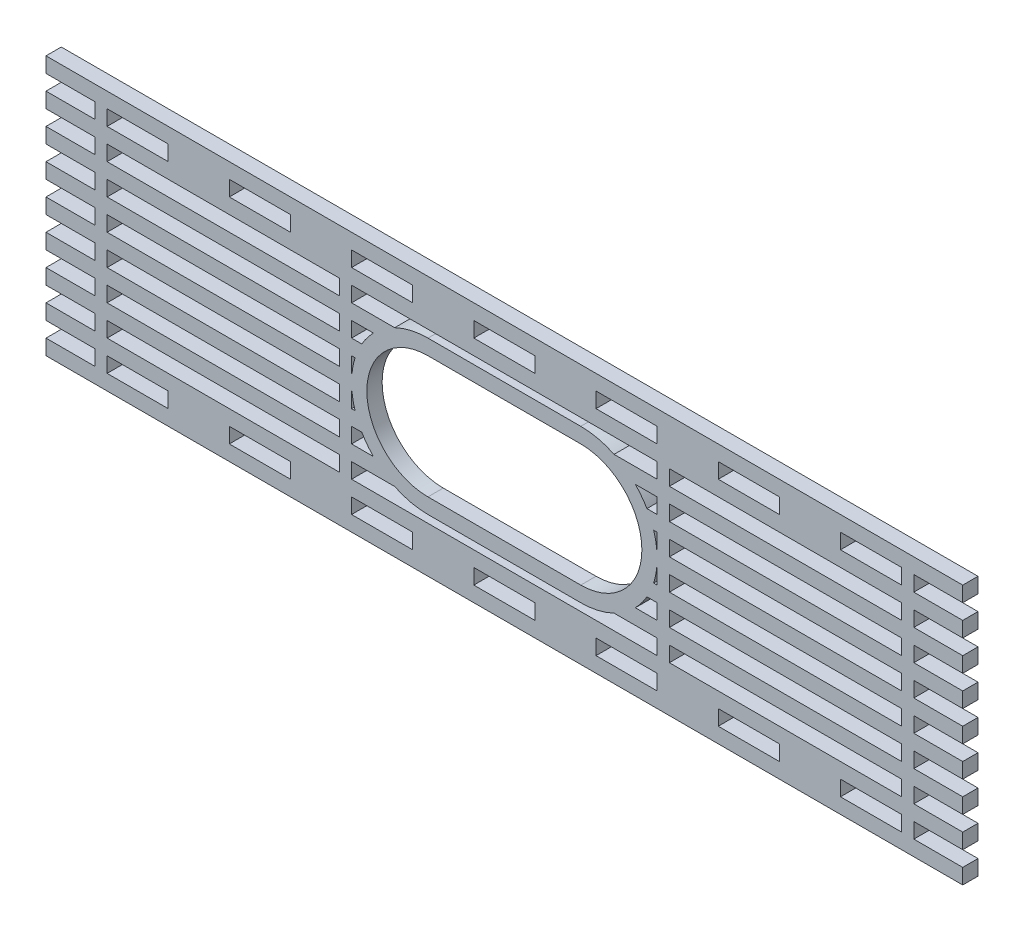
SolidWorks part; units mm, degrees
material "Maple"
ref_plane "Front Plane" through (0, 0, 0) normal (0, 0, 1) x (1, 0, 0)
ref_plane "Top Plane" through (0, 0, 0) normal (0, 1, 0) x (1, 0, 0)
ref_plane "Right Plane" through (0, 0, 0) normal (1, 0, 0) x (0, 0, -1)
sketch "Sketch1" plane through (0, 0, 0) normal (0, 0, 1) x (1, 0, 0)
  line L0 (-12.5, 0) -> (12.5, 0) construction
  line L1 (-75, -21.25) -> (75, -21.25) construction
  line L2 (-75, -21.25) -> (-75, 21.25) construction
  line L3 (-75, 21.25) -> (75, 21.25) construction
  line L4 (75, -21.25) -> (75, 21.25) construction
  line L5 (-75, -21.25) -> (75, 21.25) construction
  line L6 (-75, 21.25) -> (75, -21.25) construction
  line L7 (-12.5, 10) -> (12.5, 10)
  line L8 (-12.5, -10) -> (12.5, -10)
  line L9 (0, -10) -> (0, 10) construction
  line L10 (-22.5, 21.25) -> (-22.5, -21.25) construction
  line L11 (22.5, 21.25) -> (22.5, -21.25) construction
  line L12 (-75, 18.75) -> (-22.5, 18.75) construction
  line L13 (75, 18.75) -> (22.5, 18.75) construction
  line L14 (-75, 16.25) -> (-22.5, 16.25) construction
  line L15 (75, 16.25) -> (22.5, 16.25) construction
  line L16 (-75, 13.75) -> (-22.5, 13.75) construction
  line L18 (-75, 11.25) -> (-22.5, 11.25) construction
  line L20 (-75, 8.75) -> (-22.5, 8.75) construction
  line L22 (-75, 6.25) -> (-22.5, 6.25) construction
  line L24 (-75, 3.75) -> (-22.5, 3.75) construction
  line L26 (-75, 1.25) -> (-22.5, 1.25) construction
  line L44 (-22.5, 18.75) -> (22.5, 18.75) construction
  line L45 (-22.5, 16.25) -> (22.5, 16.25) construction
  line L46 (-22.5, 13.75) -> (22.5, 13.75) construction
  line L47 (-22.5, 11.25) -> (22.5, 11.25) construction
  line L48 (-22.5, -18.75) -> (22.5, -18.75) construction
  line L49 (-22.5, -16.25) -> (22.5, -16.25) construction
  line L50 (-22.5, -13.75) -> (22.5, -13.75) construction
  line L51 (-22.5, -11.25) -> (22.5, -11.25) construction
  line L52 (-27, 0) -> (29.3489, 0) construction
  line L53 (-5, -18.75) -> (5, -18.75)
  line L54 (-5, -18.75) -> (-5, -16.25)
  line L55 (-5, -16.25) -> (5, -16.25)
  line L56 (5, -18.75) -> (5, -16.25)
  line L57 (-5, -18.75) -> (5, -16.25) construction
  line L58 (-5, -16.25) -> (5, -18.75) construction
  line L59 (-5, 16.25) -> (5, 16.25)
  line L60 (5, 18.75) -> (5, 16.25)
  line L61 (-5, 18.75) -> (5, 18.75)
  line L62 (-5, 18.75) -> (-5, 16.25)
  line L63 (15, 16.25) -> (25, 16.25)
  line L64 (25, 18.75) -> (25, 16.25)
  line L65 (15, 18.75) -> (25, 18.75)
  line L66 (15, 18.75) -> (15, 16.25)
  line L67 (15, -18.75) -> (25, -18.75)
  line L68 (25, -18.75) -> (25, -16.25)
  line L69 (15, -16.25) -> (25, -16.25)
  line L70 (15, -18.75) -> (15, -16.25)
  line L71 (35, 16.25) -> (45, 16.25)
  line L72 (45, 18.75) -> (45, 16.25)
  line L73 (35, 18.75) -> (45, 18.75)
  line L74 (35, 18.75) -> (35, 16.25)
  line L75 (35, -18.75) -> (45, -18.75)
  line L76 (45, -18.75) -> (45, -16.25)
  line L77 (35, -16.25) -> (45, -16.25)
  line L78 (35, -18.75) -> (35, -16.25)
  line L79 (55, 16.25) -> (65, 16.25)
  line L80 (65, 18.75) -> (65, 16.25)
  line L81 (55, 18.75) -> (65, 18.75)
  line L82 (55, 18.75) -> (55, 16.25)
  line L83 (55, -18.75) -> (65, -18.75)
  line L84 (65, -18.75) -> (65, -16.25)
  line L85 (55, -16.25) -> (65, -16.25)
  line L86 (55, -18.75) -> (55, -16.25)
  line L87 (-25, -18.75) -> (-15, -18.75)
  line L88 (-15, -18.75) -> (-15, -16.25)
  line L89 (-25, -16.25) -> (-15, -16.25)
  line L90 (-25, -18.75) -> (-25, -16.25)
  line L91 (-25, 16.25) -> (-15, 16.25)
  line L92 (-15, 18.75) -> (-15, 16.25)
  line L93 (-25, 18.75) -> (-15, 18.75)
  line L94 (-25, 18.75) -> (-25, 16.25)
  line L95 (-45, -18.75) -> (-35, -18.75)
  line L96 (-35, -18.75) -> (-35, -16.25)
  line L97 (-45, -16.25) -> (-35, -16.25)
  line L98 (-45, -18.75) -> (-45, -16.25)
  line L99 (-45, 16.25) -> (-35, 16.25)
  line L100 (-35, 18.75) -> (-35, 16.25)
  line L101 (-45, 18.75) -> (-35, 18.75)
  line L102 (-45, 18.75) -> (-45, 16.25)
  line L103 (-65, -18.75) -> (-55, -18.75)
  line L104 (-55, -18.75) -> (-55, -16.25)
  line L105 (-65, -16.25) -> (-55, -16.25)
  line L106 (-65, -18.75) -> (-65, -16.25)
  line L107 (-65, 16.25) -> (-55, 16.25)
  line L108 (-55, 18.75) -> (-55, 16.25)
  line L109 (-65, 18.75) -> (-55, 18.75)
  line L110 (-65, 18.75) -> (-65, 16.25)
  line L111 (-67, 21.25) -> (-67, -21.25) construction
  line L112 (67, 21.25) -> (67, -21.25) construction
  line L113 (75, 21.25) -> (-75, 21.25)
  line L114 (-75, 21.25) -> (-75, 18.75)
  line L115 (-75, 18.75) -> (-67, 18.75)
  line L116 (-67, 18.75) -> (-67, 16.25)
  line L117 (-67, 16.25) -> (-75, 16.25)
  line L118 (-75, 16.25) -> (-75, 13.75)
  line L119 (-75, 13.75) -> (-67, 13.75)
  line L120 (-67, 13.75) -> (-67, 11.25)
  line L121 (-67, 11.25) -> (-75, 11.25)
  line L122 (-75, 11.25) -> (-75, 8.75)
  line L123 (-75, 8.75) -> (-67, 8.75)
  line L124 (-67, 8.75) -> (-67, 6.25)
  line L125 (-67, 6.25) -> (-75, 6.25)
  line L126 (-75, 6.25) -> (-75, 3.75)
  line L127 (-75, 3.75) -> (-67, 3.75)
  line L128 (-67, 3.75) -> (-67, 1.25)
  line L129 (-67, 1.25) -> (-75, 1.25)
  line L130 (-75, 1.25) -> (-75, -1.25)
  line L131 (-67, -1.25) -> (-75, -1.25)
  line L132 (-67, -3.75) -> (-67, -1.25)
  line L133 (-75, -3.75) -> (-67, -3.75)
  line L134 (-75, -6.25) -> (-75, -3.75)
  line L135 (-67, -6.25) -> (-75, -6.25)
  line L136 (-67, -8.75) -> (-67, -6.25)
  line L137 (-75, -8.75) -> (-67, -8.75)
  line L138 (-75, -11.25) -> (-75, -8.75)
  line L139 (-67, -11.25) -> (-75, -11.25)
  line L140 (-67, -13.75) -> (-67, -11.25)
  line L141 (-75, -13.75) -> (-67, -13.75)
  line L142 (-75, -16.25) -> (-75, -13.75)
  line L143 (-67, -16.25) -> (-75, -16.25)
  line L144 (-67, -18.75) -> (-67, -16.25)
  line L145 (-75, -18.75) -> (-67, -18.75)
  line L146 (-75, -21.25) -> (-75, -18.75)
  line L147 (75, -21.25) -> (-75, -21.25)
  line L148 (75, 13.75) -> (22.5, 13.75) construction
  line L149 (75, 11.25) -> (22.5, 11.25) construction
  line L150 (75, 8.75) -> (22.5, 8.75) construction
  line L151 (75, 6.25) -> (22.5, 6.25) construction
  line L152 (75, 3.75) -> (22.5, 3.75) construction
  line L153 (75, 1.25) -> (22.5, 1.25) construction
  line L228 (75, -21.25) -> (75, -18.75)
  line L229 (75, -18.75) -> (67, -18.75)
  line L230 (67, -18.75) -> (67, -16.25)
  line L231 (67, -16.25) -> (75, -16.25)
  line L232 (75, -16.25) -> (75, -13.75)
  line L233 (75, -13.75) -> (67, -13.75)
  line L234 (67, -13.75) -> (67, -11.25)
  line L235 (67, -11.25) -> (75, -11.25)
  line L236 (75, -11.25) -> (75, -8.75)
  line L237 (75, -8.75) -> (67, -8.75)
  line L238 (67, -8.75) -> (67, -6.25)
  line L239 (67, -6.25) -> (75, -6.25)
  line L240 (75, -6.25) -> (75, -3.75)
  line L241 (75, -3.75) -> (67, -3.75)
  line L242 (67, -3.75) -> (67, -1.25)
  line L243 (67, -1.25) -> (75, -1.25)
  line L244 (75, 1.25) -> (75, -1.25)
  line L245 (67, 1.25) -> (75, 1.25)
  line L246 (67, 3.75) -> (67, 1.25)
  line L247 (75, 3.75) -> (67, 3.75)
  line L248 (75, 6.25) -> (75, 3.75)
  line L249 (67, 6.25) -> (75, 6.25)
  line L250 (67, 8.75) -> (67, 6.25)
  line L251 (75, 8.75) -> (67, 8.75)
  line L252 (75, 11.25) -> (75, 8.75)
  line L253 (67, 11.25) -> (75, 11.25)
  line L254 (67, 13.75) -> (67, 11.25)
  line L255 (75, 13.75) -> (67, 13.75)
  line L256 (75, 16.25) -> (75, 13.75)
  line L257 (67, 16.25) -> (75, 16.25)
  line L258 (67, 18.75) -> (67, 16.25)
  line L259 (75, 18.75) -> (67, 18.75)
  line L260 (75, 21.25) -> (75, 18.75)
  line L261 (-12.5, 12.5) -> (12.5, 12.5)
  line L262 (-12.5, -12.5) -> (12.5, -12.5)
  line L263 (-65, 21.25) -> (-65, 1.25) construction
  line L264 (-27, 21.25) -> (-27, 1.25) construction
  line L265 (-65, 8.75) -> (-65, 6.25)
  line L266 (-65, 13.75) -> (-27, 13.75)
  line L267 (-65, 13.75) -> (-65, 11.25)
  line L268 (25, -13.75) -> (25, -11.25)
  line L269 (25, -11.25) -> (17.9486, -11.25)
  line L270 (-17.9486, -11.25) -> (-25, -11.25)
  line L271 (-25, -11.25) -> (-25, -13.75)
  line L272 (-25, -13.75) -> (25, -13.75)
  line L273 (-65, 11.25) -> (-27, 11.25)
  line L274 (-27, 13.75) -> (-27, 11.25)
  line L275 (-65, 8.75) -> (-27, 8.75)
  line L276 (-25, 11.25) -> (-25, 13.75)
  line L277 (-17.9486, 11.25) -> (-25, 11.25)
  line L278 (-27, 8.75) -> (-27, 6.25)
  line L279 (-65, 6.25) -> (-27, 6.25)
  line L280 (-65, 3.75) -> (-65, 1.25)
  line L281 (25, 11.25) -> (17.9486, 11.25)
  line L282 (25, 13.75) -> (25, 11.25)
  line L283 (-25, 13.75) -> (25, 13.75)
  line L284 (-65, 3.75) -> (-27, 3.75)
  line L285 (-27, 3.75) -> (-27, 1.25)
  line L286 (-65, 1.25) -> (-27, 1.25)
  line L287 (-65, -3.75) -> (-27, -3.75)
  line L288 (-27, -3.75) -> (-27, -1.25)
  line L289 (-65, -1.25) -> (-27, -1.25)
  line L290 (-65, -3.75) -> (-65, -1.25)
  line L291 (-65, -8.75) -> (-27, -8.75)
  line L292 (-27, -8.75) -> (-27, -6.25)
  line L293 (-65, -6.25) -> (-27, -6.25)
  line L294 (-65, -8.75) -> (-65, -6.25)
  line L295 (-65, -11.25) -> (-27, -11.25)
  line L296 (-27, -13.75) -> (-27, -11.25)
  line L297 (-65, -13.75) -> (-27, -13.75)
  line L298 (-65, -13.75) -> (-65, -11.25)
  line L299 (65, 11.25) -> (27, 11.25)
  line L300 (27, 13.75) -> (27, 11.25)
  line L301 (65, 13.75) -> (27, 13.75)
  line L302 (65, 13.75) -> (65, 11.25)
  line L303 (65, 8.75) -> (27, 8.75)
  line L304 (27, 8.75) -> (27, 6.25)
  line L305 (65, 6.25) -> (27, 6.25)
  line L306 (65, 8.75) -> (65, 6.25)
  line L307 (65, 3.75) -> (27, 3.75)
  line L308 (27, 3.75) -> (27, 1.25)
  line L309 (65, 1.25) -> (27, 1.25)
  line L310 (65, 3.75) -> (65, 1.25)
  line L311 (65, -3.75) -> (65, -1.25)
  line L312 (65, -1.25) -> (27, -1.25)
  line L313 (27, -3.75) -> (27, -1.25)
  line L314 (65, -3.75) -> (27, -3.75)
  line L315 (65, -8.75) -> (65, -6.25)
  line L316 (65, -6.25) -> (27, -6.25)
  line L317 (27, -8.75) -> (27, -6.25)
  line L318 (65, -8.75) -> (27, -8.75)
  line L319 (65, -13.75) -> (65, -11.25)
  line L320 (65, -13.75) -> (27, -13.75)
  line L321 (27, -13.75) -> (27, -11.25)
  line L322 (65, -11.25) -> (27, -11.25)
  line L323 (-21.4268, 8.75) -> (-25, 8.75)
  line L324 (-25, 8.75) -> (-25, 6.25)
  line L325 (-25, 6.25) -> (-23.3253, 6.25)
  line L326 (-24.4242, 3.75) -> (-25, 3.75)
  line L327 (-25, 3.75) -> (-25, 1.25)
  line L328 (-25, 1.25) -> (-24.9373, 1.25)
  line L329 (-25, -1.25) -> (-24.9373, -1.25)
  line L330 (-25, -3.75) -> (-25, -1.25)
  line L331 (-24.4242, -3.75) -> (-25, -3.75)
  line L332 (-25, -6.25) -> (-23.3253, -6.25)
  line L333 (-25, -8.75) -> (-25, -6.25)
  line L334 (-21.4268, -8.75) -> (-25, -8.75)
  line L335 (25, -6.25) -> (23.3253, -6.25)
  line L336 (25, -8.75) -> (25, -6.25)
  line L337 (21.4268, -8.75) -> (25, -8.75)
  line L338 (25, -1.25) -> (24.9373, -1.25)
  line L339 (25, -3.75) -> (25, -1.25)
  line L340 (24.4242, -3.75) -> (25, -3.75)
  line L341 (25, 1.25) -> (24.9373, 1.25)
  line L342 (25, 3.75) -> (25, 1.25)
  line L343 (24.4242, 3.75) -> (25, 3.75)
  line L344 (-75, -21.25) -> (-75, -18.75)
  line L345 (-75, -18.75) -> (-67, -18.75)
  line L346 (-67, -18.75) -> (-67, -16.25)
  line L347 (-67, -16.25) -> (-75, -16.25)
  line L348 (-75, -16.25) -> (-75, -13.75)
  line L349 (-75, -13.75) -> (-67, -13.75)
  line L350 (-67, -13.75) -> (-67, -11.25)
  line L351 (-67, -11.25) -> (-75, -11.25)
  line L352 (-75, -11.25) -> (-75, -8.75)
  line L353 (-75, -8.75) -> (-67, -8.75)
  line L354 (-67, -8.75) -> (-67, -6.25)
  line L355 (-67, -6.25) -> (-75, -6.25)
  line L356 (-75, -6.25) -> (-75, -3.75)
  line L357 (-75, -3.75) -> (-67, -3.75)
  line L358 (-67, -3.75) -> (-67, -1.25)
  line L359 (-67, -1.25) -> (-75, -1.25)
  line L360 (-75, 1.25) -> (-75, -1.25)
  line L361 (-67, 1.25) -> (-75, 1.25)
  line L362 (-67, 3.75) -> (-67, 1.25)
  line L363 (-75, 3.75) -> (-67, 3.75)
  line L364 (-75, 6.25) -> (-75, 3.75)
  line L365 (-67, 6.25) -> (-75, 6.25)
  line L366 (-67, 8.75) -> (-67, 6.25)
  line L367 (-75, 8.75) -> (-67, 8.75)
  line L368 (-75, 11.25) -> (-75, 8.75)
  line L369 (-67, 11.25) -> (-75, 11.25)
  line L370 (-67, 13.75) -> (-67, 11.25)
  line L371 (-75, 13.75) -> (-67, 13.75)
  line L372 (-75, 16.25) -> (-75, 13.75)
  line L373 (-67, 16.25) -> (-75, 16.25)
  line L374 (-67, 18.75) -> (-67, 16.25)
  line L375 (-75, 18.75) -> (-67, 18.75)
  line L376 (-75, 21.25) -> (-75, 18.75)
  line L377 (75, 21.25) -> (75, 18.75)
  line L378 (75, 18.75) -> (67, 18.75)
  line L379 (67, 18.75) -> (67, 16.25)
  line L380 (67, 16.25) -> (75, 16.25)
  line L381 (75, 16.25) -> (75, 13.75)
  line L382 (75, 13.75) -> (67, 13.75)
  line L383 (67, 13.75) -> (67, 11.25)
  line L384 (67, 11.25) -> (75, 11.25)
  line L385 (75, 11.25) -> (75, 8.75)
  line L386 (75, 8.75) -> (67, 8.75)
  line L387 (67, 8.75) -> (67, 6.25)
  line L388 (67, 6.25) -> (75, 6.25)
  line L389 (75, 6.25) -> (75, 3.75)
  line L390 (75, 3.75) -> (67, 3.75)
  line L391 (67, 3.75) -> (67, 1.25)
  line L392 (67, 1.25) -> (75, 1.25)
  line L393 (75, 1.25) -> (75, -1.25)
  line L394 (67, -1.25) -> (75, -1.25)
  line L395 (67, -3.75) -> (67, -1.25)
  line L396 (75, -3.75) -> (67, -3.75)
  line L397 (75, -6.25) -> (75, -3.75)
  line L398 (67, -6.25) -> (75, -6.25)
  line L399 (67, -8.75) -> (67, -6.25)
  line L400 (75, -8.75) -> (67, -8.75)
  line L401 (75, -11.25) -> (75, -8.75)
  line L402 (67, -11.25) -> (75, -11.25)
  line L403 (67, -13.75) -> (67, -11.25)
  line L404 (75, -13.75) -> (67, -13.75)
  line L405 (75, -16.25) -> (75, -13.75)
  line L406 (67, -16.25) -> (75, -16.25)
  line L407 (67, -18.75) -> (67, -16.25)
  line L408 (75, -18.75) -> (67, -18.75)
  line L409 (75, -21.25) -> (75, -18.75)
  line L410 (25, 6.25) -> (23.3253, 6.25)
  line L411 (25, 8.75) -> (25, 6.25)
  line L412 (21.4268, 8.75) -> (25, 8.75)
  arc A0 (-12.5, 10) -> (-12.5, -10) centre (-12.5, 0) ccw
  arc A1 (12.5, -10) -> (12.5, 10) centre (12.5, 0) ccw
  arc A2 (12.5, -12.5) -> (12.5, 12.5) centre (12.5, 0) ccw
  arc A3 (-12.5, 12.5) -> (-12.5, -12.5) centre (-12.5, 0) ccw
  point P0 (0, 0)
  point P8 (0, 0)
  point P23 (0, -17.5)
  point P159 (-75, 0)
  point P218 (-24.9374, 1.2492)
  point P255 (0, -21.25)
  point P285 (0, 21.25)
  dimension "D3" = 10
  dimension "D1" = 42.5
  dimension "D2" = 150
  dimension "D4" = 25
  dimension "D5" = 2.5
  dimension "D7" = 2.5
  dimension "D10" = 10
  dimension "D12" = 10
  dimension "D14" = 10
  dimension "D15" = 2
  dimension "D16" = 2.5
  dimension "D17" = 2.5
  dimension "D18" = 2.5
  dimension "D19" = 2
  dimension "D20" = 2.5
  dimension "D6" = 8
  dimension "D8" = 4
  dimension "D9" = 4
  dimension "D11" = 4
  dimension "D13" = 4
  dimension "D21" = 3
extrude "Boss-Extrude1" add sketch "Sketch1" along normal mid plane 2.5 contours L260 L113 L114 L115 L116 L117 L118 L119 L120 L121 L122 L123 L124 L125 L126 L127 L128 L129 L130 L131 L132 L133 L134 L135 L136 L137 L138 L139 L140 L141 L142 L143 L144 L145 L146 L147 L228 L229 L230 L231 L232 L233 L234 L235 L236 L237 L238 L239 L240 L241 L242 | L261 A3 L262 A2 A1 L8 A0 L7
